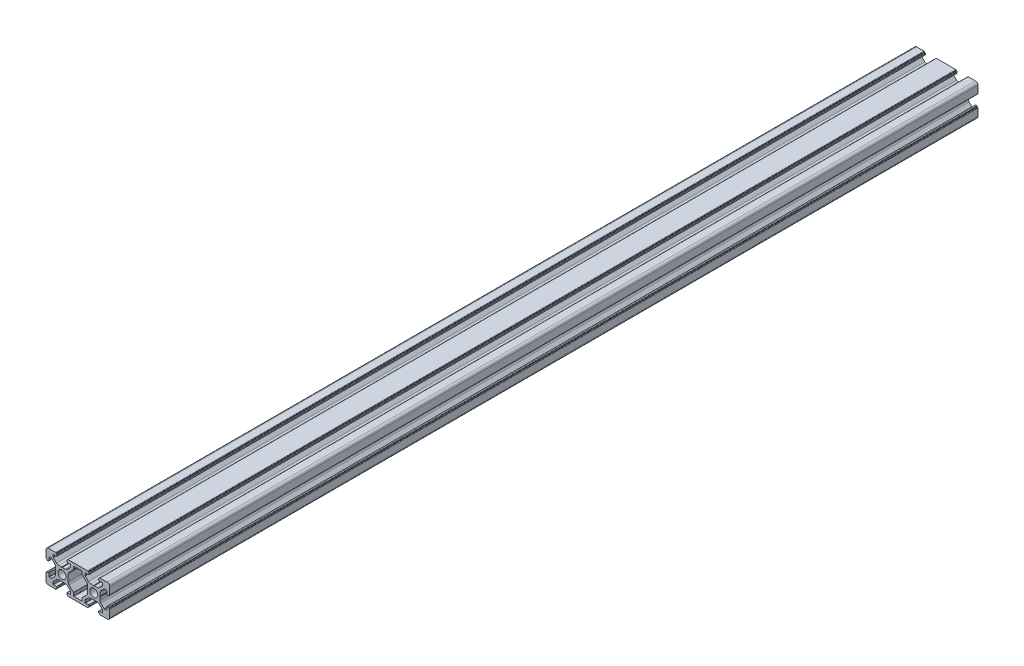
SolidWorks part; units mm, degrees
ref_plane "前视基准面" through (0, 0, 0) normal (0, 0, 1) x (1, 0, 0)
ref_plane "上视基准面" through (0, 0, 0) normal (0, 1, 0) x (1, 0, 0)
ref_plane "右视基准面" through (0, 0, 0) normal (1, 0, 0) x (0, 0, -1)
sketch "草图1" plane through (0, 0, 0) normal (0, 0, 1) x (1, 0, 0)
  line L0 (-2.7, -6.3636) -> (-2.7, -7.9)
  line L1 (-5.5142, -3.4251) -> (-2.7879, -6.1515)
  line L2 (-2.4, -8.2) -> (2.4, -8.2)
  line L3 (-6.1, 0) -> (-6.1, -2.0109)
  line L4 (-6.1, 2.0109) -> (-6.1, 0)
  line L5 (2.7, -6.3636) -> (2.7, -7.9)
  line L6 (-2.7879, 6.1515) -> (-5.5142, 3.4251)
  line L7 (5.5142, -3.4251) -> (2.7879, -6.1515)
  line L8 (-2.7, 6.3636) -> (-2.7, 7.9)
  line L9 (6.1, 0) -> (6.1, -2.0109)
  line L10 (6.1, 2.0109) -> (6.1, 0)
  line L11 (-2.4, 8.2) -> (2.4, 8.2)
  line L12 (2.7879, 6.1515) -> (5.5142, 3.4251)
  line L13 (2.7, 6.3636) -> (2.7, 7.9)
  line L14 (4.5, -6.6849) -> (4.5, -7.9)
  line L15 (4.8, -8.2) -> (6.6, -8.2)
  line L16 (6.9, -8.5) -> (6.9, -9.2)
  line L17 (6.6, -9.5) -> (6.4, -9.5)
  line L18 (6.4, -9.5) -> (6.4, -9.7)
  line L19 (6.1, -10) -> (-6.1, -10)
  line L20 (-6.4, -9.7) -> (-6.4, -9.5)
  line L21 (-6.4, -9.5) -> (-6.6, -9.5)
  line L22 (-6.9, -9.2) -> (-6.9, -8.5)
  line L23 (-6.6, -8.2) -> (-4.8, -8.2)
  line L24 (-4.5, -7.9) -> (-4.5, -6.6849)
  line L25 (-4.5879, -6.4728) -> (-6.5749, -4.4858)
  line L26 (-7.9891, -3.9) -> (-9.8, -3.9)
  line L27 (-9.8, -3.9) -> (-10, -3.7)
  line L28 (-10, -3.7) -> (-10.2, -3.9)
  line L29 (-10.2, -3.9) -> (-12.0109, -3.9)
  line L30 (-13.4251, -4.4858) -> (-15.4121, -6.4728)
  line L31 (-15.5, -6.6849) -> (-15.5, -7.9)
  line L32 (-15.2, -8.2) -> (-13.4, -8.2)
  line L33 (-13.1, -8.5) -> (-13.1, -9.2)
  line L34 (-13.4, -9.5) -> (-13.6, -9.5)
  line L35 (-13.6, -9.5) -> (-13.6, -9.7)
  line L36 (-13.9, -10) -> (-18.5, -10)
  line L37 (-20, -8.5) -> (-20, -3.9)
  line L38 (-19.7, -3.6) -> (-19.5, -3.6)
  line L39 (-19.5, -3.6) -> (-19.5, -3.4)
  line L40 (-19.2, -3.1) -> (-18.5, -3.1)
  line L41 (-18.2, -3.4) -> (-18.2, -5.2)
  line L42 (-17.9, -5.5) -> (-16.6849, -5.5)
  line L43 (-16.4728, -5.4121) -> (-14.4858, -3.4251)
  line L44 (-13.9, -2.0109) -> (-13.9, -0.2)
  line L45 (-13.9, -0.2) -> (-13.7, 0)
  line L46 (-13.7, 0) -> (-13.9, 0.2)
  line L47 (-13.9, 0.2) -> (-13.9, 2.0109)
  line L48 (-14.4858, 3.4251) -> (-16.4728, 5.4121)
  line L49 (-16.6849, 5.5) -> (-17.9, 5.5)
  line L50 (-18.2, 5.2) -> (-18.2, 3.4)
  line L51 (-18.5, 3.1) -> (-19.2, 3.1)
  line L52 (-19.5, 3.4) -> (-19.5, 3.6)
  line L53 (-19.5, 3.6) -> (-19.7, 3.6)
  line L54 (-20, 3.9) -> (-20, 8.5)
  line L55 (-18.5, 10) -> (-13.9, 10)
  line L56 (-13.6, 9.7) -> (-13.6, 9.5)
  line L57 (-13.6, 9.5) -> (-13.4, 9.5)
  line L58 (-13.1, 9.2) -> (-13.1, 8.5)
  line L59 (-13.4, 8.2) -> (-15.2, 8.2)
  line L60 (-15.5, 7.9) -> (-15.5, 6.6849)
  line L61 (-15.4121, 6.4728) -> (-13.4251, 4.4858)
  line L62 (-12.0109, 3.9) -> (-10.2, 3.9)
  line L63 (-10.2, 3.9) -> (-10, 3.7)
  line L64 (-10, 3.7) -> (-9.8, 3.9)
  line L65 (-9.8, 3.9) -> (-7.9891, 3.9)
  line L66 (-6.5749, 4.4858) -> (-4.5879, 6.4728)
  line L67 (-4.5, 6.6849) -> (-4.5, 7.9)
  line L68 (-4.8, 8.2) -> (-6.6, 8.2)
  line L69 (-6.9, 8.5) -> (-6.9, 9.2)
  line L70 (-6.6, 9.5) -> (-6.4, 9.5)
  line L71 (-6.4, 9.5) -> (-6.4, 9.7)
  line L72 (-6.1, 10) -> (6.1, 10)
  line L73 (6.4, 9.7) -> (6.4, 9.5)
  line L74 (6.4, 9.5) -> (6.6, 9.5)
  line L75 (6.9, 9.2) -> (6.9, 8.5)
  line L76 (6.6, 8.2) -> (4.8, 8.2)
  line L77 (4.5, 7.9) -> (4.5, 6.6849)
  line L78 (4.5879, 6.4728) -> (6.5749, 4.4858)
  line L79 (7.9891, 3.9) -> (9.8, 3.9)
  line L80 (9.8, 3.9) -> (10, 3.7)
  line L81 (10, 3.7) -> (10.2, 3.9)
  line L82 (10.2, 3.9) -> (12.0109, 3.9)
  line L83 (13.4251, 4.4858) -> (15.4121, 6.4728)
  line L84 (15.5, 6.6849) -> (15.5, 7.9)
  line L85 (15.2, 8.2) -> (13.4, 8.2)
  line L86 (13.1, 8.5) -> (13.1, 9.2)
  line L87 (13.4, 9.5) -> (13.6, 9.5)
  line L88 (13.6, 9.5) -> (13.6, 9.7)
  line L89 (13.9, 10) -> (18.5, 10)
  line L90 (20, 8.5) -> (20, 3.9)
  line L91 (19.7, 3.6) -> (19.5, 3.6)
  line L92 (19.5, 3.6) -> (19.5, 3.4)
  line L93 (19.2, 3.1) -> (18.5, 3.1)
  line L94 (18.2, 3.4) -> (18.2, 5.2)
  line L95 (17.9, 5.5) -> (16.6849, 5.5)
  line L96 (16.4728, 5.4121) -> (14.4858, 3.4251)
  line L97 (13.9, 2.0109) -> (13.9, 0.2)
  line L98 (13.9, 0.2) -> (13.7, 0)
  line L99 (13.7, 0) -> (13.9, -0.2)
  line L100 (13.9, -0.2) -> (13.9, -2.0109)
  line L101 (14.4858, -3.4251) -> (16.4728, -5.4121)
  line L102 (16.6849, -5.5) -> (17.9, -5.5)
  line L103 (18.2, -5.2) -> (18.2, -3.4)
  line L104 (18.5, -3.1) -> (19.2, -3.1)
  line L105 (19.5, -3.4) -> (19.5, -3.6)
  line L106 (19.5, -3.6) -> (19.7, -3.6)
  line L107 (20, -3.9) -> (20, -8.5)
  line L108 (18.5, -10) -> (13.9, -10)
  line L109 (13.6, -9.7) -> (13.6, -9.5)
  line L110 (13.6, -9.5) -> (13.4, -9.5)
  line L111 (13.1, -9.2) -> (13.1, -8.5)
  line L112 (13.4, -8.2) -> (15.2, -8.2)
  line L113 (15.5, -7.9) -> (15.5, -6.6849)
  line L114 (15.4121, -6.4728) -> (13.4251, -4.4858)
  line L115 (12.0109, -3.9) -> (10.2, -3.9)
  line L116 (10.2, -3.9) -> (10, -3.7)
  line L117 (10, -3.7) -> (9.8, -3.9)
  line L118 (9.8, -3.9) -> (7.9891, -3.9)
  line L119 (6.5749, -4.4858) -> (4.5879, -6.4728)
  arc A0 (-2.7, -6.3636) -> (-2.7879, -6.1515) centre (-3, -6.3636) ccw
  arc A1 (-2.7, -7.9) -> (-2.4, -8.2) centre (-2.4, -7.9) ccw
  arc A2 (-6.1, -2.0109) -> (-5.5142, -3.4251) centre (-4.1, -2.0109) ccw
  arc A3 (2.4, -8.2) -> (2.7, -7.9) centre (2.4, -7.9) ccw
  arc A4 (-5.5142, 3.4251) -> (-6.1, 2.0109) centre (-4.1, 2.0109) ccw
  arc A5 (2.7879, -6.1515) -> (2.7, -6.3636) centre (3, -6.3636) ccw
  arc A6 (-2.7879, 6.1515) -> (-2.7, 6.3636) centre (-3, 6.3636) ccw
  arc A7 (5.5142, -3.4251) -> (6.1, -2.0109) centre (4.1, -2.0109) ccw
  arc A8 (-2.4, 8.2) -> (-2.7, 7.9) centre (-2.4, 7.9) ccw
  arc A9 (6.1, 2.0109) -> (5.5142, 3.4251) centre (4.1, 2.0109) ccw
  arc A10 (2.7, 7.9) -> (2.4, 8.2) centre (2.4, 7.9) ccw
  arc A11 (2.7, 6.3636) -> (2.7879, 6.1515) centre (3, 6.3636) ccw
  arc A12 (4.5, -7.9) -> (4.8, -8.2) centre (4.8, -7.9) ccw
  arc A13 (6.9, -8.5) -> (6.6, -8.2) centre (6.6, -8.5) ccw
  arc A14 (6.6, -9.5) -> (6.9, -9.2) centre (6.6, -9.2) ccw
  arc A15 (6.1, -10) -> (6.4, -9.7) centre (6.1, -9.7) ccw
  arc A16 (-6.4, -9.7) -> (-6.1, -10) centre (-6.1, -9.7) ccw
  arc A17 (-6.9, -9.2) -> (-6.6, -9.5) centre (-6.6, -9.2) ccw
  arc A18 (-6.6, -8.2) -> (-6.9, -8.5) centre (-6.6, -8.5) ccw
  arc A19 (-4.8, -8.2) -> (-4.5, -7.9) centre (-4.8, -7.9) ccw
  arc A20 (-4.5, -6.6849) -> (-4.5879, -6.4728) centre (-4.8, -6.6849) ccw
  arc A21 (-6.5749, -4.4858) -> (-7.9891, -3.9) centre (-7.9891, -5.9) ccw
  arc A22 (-12.0109, -3.9) -> (-13.4251, -4.4858) centre (-12.0109, -5.9) ccw
  arc A23 (-15.4121, -6.4728) -> (-15.5, -6.6849) centre (-15.2, -6.6849) ccw
  arc A24 (-15.5, -7.9) -> (-15.2, -8.2) centre (-15.2, -7.9) ccw
  arc A25 (-13.1, -8.5) -> (-13.4, -8.2) centre (-13.4, -8.5) ccw
  arc A26 (-13.4, -9.5) -> (-13.1, -9.2) centre (-13.4, -9.2) ccw
  arc A27 (-13.9, -10) -> (-13.6, -9.7) centre (-13.9, -9.7) ccw
  arc A28 (-20, -8.5) -> (-18.5, -10) centre (-18.5, -8.5) ccw
  arc A29 (-19.7, -3.6) -> (-20, -3.9) centre (-19.7, -3.9) ccw
  arc A30 (-19.2, -3.1) -> (-19.5, -3.4) centre (-19.2, -3.4) ccw
  arc A31 (-18.2, -3.4) -> (-18.5, -3.1) centre (-18.5, -3.4) ccw
  arc A32 (-18.2, -5.2) -> (-17.9, -5.5) centre (-17.9, -5.2) ccw
  arc A33 (-16.6849, -5.5) -> (-16.4728, -5.4121) centre (-16.6849, -5.2) ccw
  arc A34 (-14.4858, -3.4251) -> (-13.9, -2.0109) centre (-15.9, -2.0109) ccw
  arc A35 (-13.9, 2.0109) -> (-14.4858, 3.4251) centre (-15.9, 2.0109) ccw
  arc A36 (-16.4728, 5.4121) -> (-16.6849, 5.5) centre (-16.6849, 5.2) ccw
  arc A37 (-17.9, 5.5) -> (-18.2, 5.2) centre (-17.9, 5.2) ccw
  arc A38 (-18.5, 3.1) -> (-18.2, 3.4) centre (-18.5, 3.4) ccw
  arc A39 (-19.5, 3.4) -> (-19.2, 3.1) centre (-19.2, 3.4) ccw
  arc A40 (-20, 3.9) -> (-19.7, 3.6) centre (-19.7, 3.9) ccw
  arc A41 (-18.5, 10) -> (-20, 8.5) centre (-18.5, 8.5) ccw
  arc A42 (-13.6, 9.7) -> (-13.9, 10) centre (-13.9, 9.7) ccw
  arc A43 (-13.1, 9.2) -> (-13.4, 9.5) centre (-13.4, 9.2) ccw
  arc A44 (-13.4, 8.2) -> (-13.1, 8.5) centre (-13.4, 8.5) ccw
  arc A45 (-15.2, 8.2) -> (-15.5, 7.9) centre (-15.2, 7.9) ccw
  arc A46 (-15.5, 6.6849) -> (-15.4121, 6.4728) centre (-15.2, 6.6849) ccw
  arc A47 (-13.4251, 4.4858) -> (-12.0109, 3.9) centre (-12.0109, 5.9) ccw
  arc A48 (-7.9891, 3.9) -> (-6.5749, 4.4858) centre (-7.9891, 5.9) ccw
  arc A49 (-4.5879, 6.4728) -> (-4.5, 6.6849) centre (-4.8, 6.6849) ccw
  arc A50 (-4.5, 7.9) -> (-4.8, 8.2) centre (-4.8, 7.9) ccw
  arc A51 (-6.9, 8.5) -> (-6.6, 8.2) centre (-6.6, 8.5) ccw
  arc A52 (-6.6, 9.5) -> (-6.9, 9.2) centre (-6.6, 9.2) ccw
  arc A53 (-6.1, 10) -> (-6.4, 9.7) centre (-6.1, 9.7) ccw
  arc A54 (6.4, 9.7) -> (6.1, 10) centre (6.1, 9.7) ccw
  arc A55 (6.9, 9.2) -> (6.6, 9.5) centre (6.6, 9.2) ccw
  arc A56 (6.6, 8.2) -> (6.9, 8.5) centre (6.6, 8.5) ccw
  arc A57 (4.8, 8.2) -> (4.5, 7.9) centre (4.8, 7.9) ccw
  arc A58 (4.5, 6.6849) -> (4.5879, 6.4728) centre (4.8, 6.6849) ccw
  arc A59 (6.5749, 4.4858) -> (7.9891, 3.9) centre (7.9891, 5.9) ccw
  arc A60 (12.0109, 3.9) -> (13.4251, 4.4858) centre (12.0109, 5.9) ccw
  arc A61 (15.4121, 6.4728) -> (15.5, 6.6849) centre (15.2, 6.6849) ccw
  arc A62 (15.5, 7.9) -> (15.2, 8.2) centre (15.2, 7.9) ccw
  arc A63 (13.1, 8.5) -> (13.4, 8.2) centre (13.4, 8.5) ccw
  arc A64 (13.4, 9.5) -> (13.1, 9.2) centre (13.4, 9.2) ccw
  arc A65 (13.9, 10) -> (13.6, 9.7) centre (13.9, 9.7) ccw
  arc A66 (20, 8.5) -> (18.5, 10) centre (18.5, 8.5) ccw
  arc A67 (19.7, 3.6) -> (20, 3.9) centre (19.7, 3.9) ccw
  arc A68 (19.2, 3.1) -> (19.5, 3.4) centre (19.2, 3.4) ccw
  arc A69 (18.2, 3.4) -> (18.5, 3.1) centre (18.5, 3.4) ccw
  arc A70 (18.2, 5.2) -> (17.9, 5.5) centre (17.9, 5.2) ccw
  arc A71 (16.6849, 5.5) -> (16.4728, 5.4121) centre (16.6849, 5.2) ccw
  arc A72 (14.4858, 3.4251) -> (13.9, 2.0109) centre (15.9, 2.0109) ccw
  arc A73 (13.9, -2.0109) -> (14.4858, -3.4251) centre (15.9, -2.0109) ccw
  arc A74 (16.4728, -5.4121) -> (16.6849, -5.5) centre (16.6849, -5.2) ccw
  arc A75 (17.9, -5.5) -> (18.2, -5.2) centre (17.9, -5.2) ccw
  arc A76 (18.5, -3.1) -> (18.2, -3.4) centre (18.5, -3.4) ccw
  arc A77 (19.5, -3.4) -> (19.2, -3.1) centre (19.2, -3.4) ccw
  arc A78 (20, -3.9) -> (19.7, -3.6) centre (19.7, -3.9) ccw
  arc A79 (18.5, -10) -> (20, -8.5) centre (18.5, -8.5) ccw
  arc A80 (13.6, -9.7) -> (13.9, -10) centre (13.9, -9.7) ccw
  arc A81 (13.1, -9.2) -> (13.4, -9.5) centre (13.4, -9.2) ccw
  arc A82 (13.4, -8.2) -> (13.1, -8.5) centre (13.4, -8.5) ccw
  arc A83 (15.2, -8.2) -> (15.5, -7.9) centre (15.2, -7.9) ccw
  arc A84 (15.5, -6.6849) -> (15.4121, -6.4728) centre (15.2, -6.6849) ccw
  arc A85 (13.4251, -4.4858) -> (12.0109, -3.9) centre (12.0109, -5.9) ccw
  arc A86 (7.9891, -3.9) -> (6.5749, -4.4858) centre (7.9891, -5.9) ccw
  arc A87 (4.5879, -6.4728) -> (4.5, -6.6849) centre (4.8, -6.6849) ccw
  circle A88 centre (10, 0) radius 2.5
  circle A89 centre (-10, 0) radius 2.5
extrude "凸台-拉伸1" add sketch "草图1" along normal blind 545
